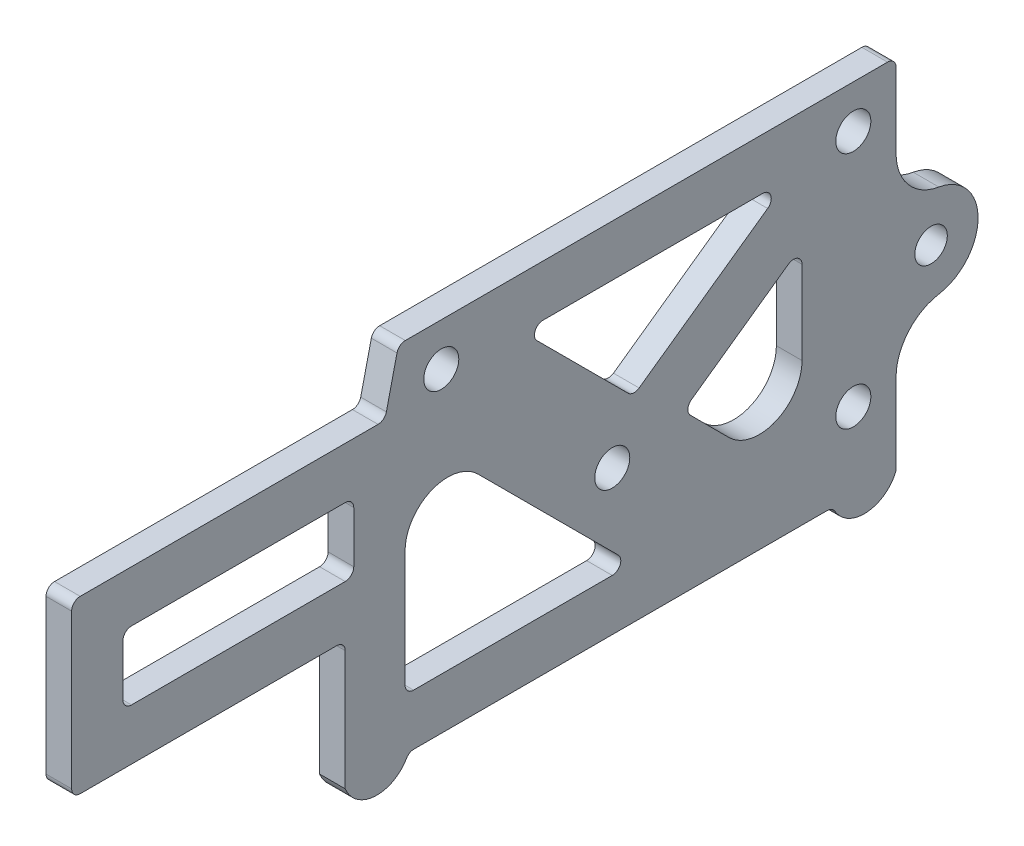
SolidWorks part; units mm, degrees
ref_plane "前视基准面" through (0, 0, 0) normal (0, 0, 1) x (1, 0, 0)
ref_plane "上视基准面" through (0, 0, 0) normal (0, 1, 0) x (1, 0, 0)
ref_plane "右视基准面" through (0, 0, 0) normal (1, 0, 0) x (0, 0, -1)
sketch "草图1" plane through (0, 0, 0) normal (1, 0, 0) x (0, 0, -1)
  line L0 (8.9, -22.95) -> (-35.336, -22.95) construction
  line L1 (24.1, -13.95) -> (-24.1, -13.95) construction
  line L2 (24.1, -13.95) -> (24.1, 13.95) construction
  line L3 (24.1, 13.95) -> (-24.1, 13.95) construction
  line L4 (-24.1, -13.95) -> (-24.1, 13.95) construction
  line L5 (0, 13.95) -> (0, -13.95) construction
  line L6 (24.1, 0) -> (-24.1, 0) construction
  line L7 (29.1, -22.95) -> (8.9, -22.95) construction
  line L8 (29.1, -22.95) -> (29.1, -7.6302)
  line L9 (29.1, 18.95) -> (-29.1, 18.95)
  line L11 (0, 18.95) -> (0, -18.95) construction
  line L12 (29.1, 0) -> (-29.1, 0) construction
  line L13 (-4.1, -6.05) -> (32.9383, -11.9163) construction
  line L14 (-4.1, -6.05) -> (39.9248, -1.4228) construction
  line L15 (33.1946, -7.6302) -> (29.1, -7.6302)
  line L16 (33.1946, 3.3698) -> (29.1, 3.3698)
  line L17 (29.1, 3.3698) -> (29.1, 18.95)
  line L18 (31.305, -2.3288) -> (33.1946, -2.1302) construction
  line L21 (-35.336, -7.95) -> (-67.336, -7.95)
  line L22 (-67.336, -7.95) -> (-67.336, 12.05)
  line L23 (-67.336, 12.05) -> (-30.6996, 12.05)
  line L24 (-30.6996, 12.05) -> (-29.1, 18.95)
  line L25 (-35.336, -7.95) -> (-35.336, -22.95)
  line L26 (-27.9198, -22.95) -> (21.6838, -22.95)
  circle A0 centre (-24.1, 13.95) radius 2.05
  circle A1 centre (24.1, 13.95) radius 2.05
  circle A2 centre (24.1, -13.95) radius 2.05
  circle A3 centre (-24.1, -13.95) radius 2.05 construction
  circle A4 centre (-4.1, -6.05) radius 2.05
  circle A7 centre (-4.1, -6.05) radius 37.5 construction
  circle A8 centre (32.9383, -11.9163) radius 1.9 construction
  circle A9 centre (33.1946, -2.1302) radius 1.9
  arc A10 (33.1946, -7.6302) -> (33.1946, 3.3698) centre (33.1946, -2.1302) ccw
  arc A11 (-35.336, -22.95) -> (-27.9198, -22.95) centre (-31.6279, -21.45) ccw
  arc A12 (21.6838, -22.95) -> (29.1, -22.95) centre (25.3919, -21.45) ccw
  point P0 (0, 0)
  point P10 (0, 0)
  dimension "D3" = 4.1
  dimension "D6" = 4.1
  dimension "D9" = 75
  dimension "D10" = 3.8
  dimension "D12" = 11
  dimension "D19" = 4
  dimension "D1" = 27.9
  dimension "D2" = 48.2
  dimension "D4" = 20
  dimension "D5" = 20
  dimension "D7" = 6
  dimension "D8" = 5
  dimension "D11" = 15
  dimension "D13" = 6
  dimension "D14" = 32
  dimension "D15" = 9
  dimension "D16" = 5
  dimension "D17" = 20
  dimension "D18" = 9
  dimension "D20" = 1.5
extrude "凸台-拉伸1" add sketch "草图1" along normal blind 3
sketch "草图2" plane through (3, 0, 0) normal (1, 0, 0) x (0, 0, -1)
  line L0 (-28.336, 9.7008) -> (-28.336, -16.95)
  line L1 (-34.336, -1.95) -> (-61.336, -1.95)
  line L2 (-34.336, -1.95) -> (-34.336, 6.05)
  line L3 (-34.336, 6.05) -> (-61.336, 6.05)
  line L4 (-61.336, -1.95) -> (-61.336, 6.05)
  line L5 (-47.836, 6.05) -> (-47.836, -1.95) construction
  line L6 (-34.336, 2.05) -> (-61.336, 2.05) construction
  line L7 (-28.336, -16.95) -> (-1.6853, -16.95)
  line L8 (-1.6853, -16.95) -> (-28.336, 9.7008)
  line L9 (18.1, 5.4038) -> (4.2023, -4.4528)
  line L10 (4.2023, -4.4528) -> (18.1, -18.3505)
  line L11 (18.1, -18.3505) -> (18.1, 5.4038)
  line L12 (-14.6147, 12.95) -> (16.6399, 12.95)
  line L13 (16.6399, 12.95) -> (-1.646, -0.0187)
  line L14 (-1.646, -0.0187) -> (-14.6147, 12.95)
  line L15 (-24.1, 13.95) -> (-4.1, -6.05) construction
  line L16 (-35.336, -7.95) -> (-35.336, -22.95) construction
  line L17 (-27.9198, -22.95) -> (21.6838, -22.95) construction
  line L18 (29.1, 18.95) -> (-29.1, 18.95) construction
  line L19 (24.1, 13.95) -> (-4.1, -6.05) construction
  line L20 (-67.336, 12.05) -> (-67.336, -7.95) construction
  line L21 (-30.6996, 12.05) -> (-67.336, 12.05) construction
  line L22 (-67.336, -7.95) -> (-35.336, -7.95) construction
  circle A0 centre (24.1, -13.95) radius 2.05 construction
  point P0 (-47.836, 2.05)
  dimension "D1" = 12
  dimension "D2" = 7
  dimension "D3" = 6
  dimension "D4" = 6
  dimension "D5" = 7
  dimension "D6" = 6
  dimension "D7" = 1
  dimension "D8" = 6
  dimension "D9" = 6
  dimension "D10" = 6
  dimension "D11" = 6
extrude "切除-拉伸1" cut sketch "草图2" against normal blind 3
fillet "圆角1" radius 5 2 edges at (1.5, 9.7008, 28.336) (1.5, -18.3505, -18.1)
fillet "圆角2" radius 1 19 edges at (1.5, -7.95, 67.336) (1.5, 12.05, 67.336) (1.5, -0.0187, 1.646) (1.5, 12.95, -16.6399) (1.5, 12.95, 14.6147) (1.5, 5.4038, -18.1) (1.5, -4.4528, -4.2023) (1.5, -16.95, 1.6853) (1.5, -22.95, -21.6838) (1.5, -22.95, 27.9198) (1.5, -7.95, 35.336) (1.5, 12.05, 30.6996) (1.5, -16.95, 28.336) (1.5, 6.05, 34.336) (1.5, -1.95, 34.336) (1.5, -1.95, 61.336) (1.5, 6.05, 61.336) (1.5, 18.95, 29.1) (1.5, 18.95, -29.1)
fillet "圆角3" radius 6 2 edges at (1.5, -7.6302, -29.1) (1.5, 3.3698, -29.1)
sketch "草图3" plane through (3, 0, 0) normal (1, 0, 0) x (0, 0, -1)
  line L0 (29.1, 9.2109) -> (29.1, 17.95) construction
  line L1 (87.3507, -31.175) -> (29.1, -31.175)
  line L2 (87.3507, -31.175) -> (87.3507, 20.3144)
  line L3 (87.3507, 20.3144) -> (29.1, 20.3144)
  line L4 (29.1, -31.175) -> (29.1, 20.3144)
  line L5 (58.2253, 20.3144) -> (58.2253, -31.175) construction
  line L6 (87.3507, -5.4303) -> (29.1, -5.4303) construction
  point P0 (58.2253, -5.4303)
extrude "切除-拉伸2" [suppressed] cut sketch "草图3" against normal blind 3
sketch "草图4" plane through (3, 0, 0) normal (1, 0, 0) x (0, 0, -1)
  line L0 (-29.2795, 18.1758) -> (-35.336, -4.95)
  line L1 (-35.336, -4.95) -> (-35.336, -8.95)
  line L2 (-29.2795, 18.1758) -> (-73.8303, 18.1758)
  line L3 (-73.8303, 18.1758) -> (-73.8303, -8.95)
  line L4 (-73.8303, -8.95) -> (-35.336, -8.95)
  line L5 (29.1, 9.2109) -> (29.1, -13.4712)
  line L6 (29.1, -13.4712) -> (55.6085, -13.4712)
  line L7 (55.6085, -13.4712) -> (55.6085, 9.2109)
  line L8 (55.6085, 9.2109) -> (29.1, 9.2109)
  line L9 (-13.1244, 12.3327) -> (-25.2495, 2.2491)
  line L10 (-25.2495, 2.2491) -> (-3.1756, -16.3327)
  line L11 (-3.1756, -16.3327) -> (15.0134, -10.8988)
  line L12 (15.0134, -10.8988) -> (17.5591, 4.357)
  line L13 (17.5591, 4.357) -> (14.4541, 12.2536)
  line L14 (14.4541, 12.2536) -> (-13.1244, 12.3327)
  arc A5 (18.1, 3.4686) -> (16.5215, 4.2843) centre (17.1, 3.4686) ccw construction
  arc A6 (14.0797, 11.1343) -> (13.5012, 12.95) centre (13.5012, 11.95) ccw construction
  arc A9 (-12.2005, 12.95) -> (-12.9076, 11.2429) centre (-12.2005, 11.95) ccw construction
  arc A10 (-19.8005, 1.1652) -> (-28.336, -2.3703) centre (-23.336, -2.3703) ccw construction
  arc A11 (9.5645, -9.815) -> (18.1, -6.2794) centre (13.1, -6.2794) ccw construction
  arc A12 (-4.0995, -16.95) -> (-3.3924, -15.2429) centre (-4.0995, -15.95) ccw construction
  dimension "D1" = 4
extrude "切除-拉伸3" [suppressed] cut sketch "草图4" against normal blind 3
